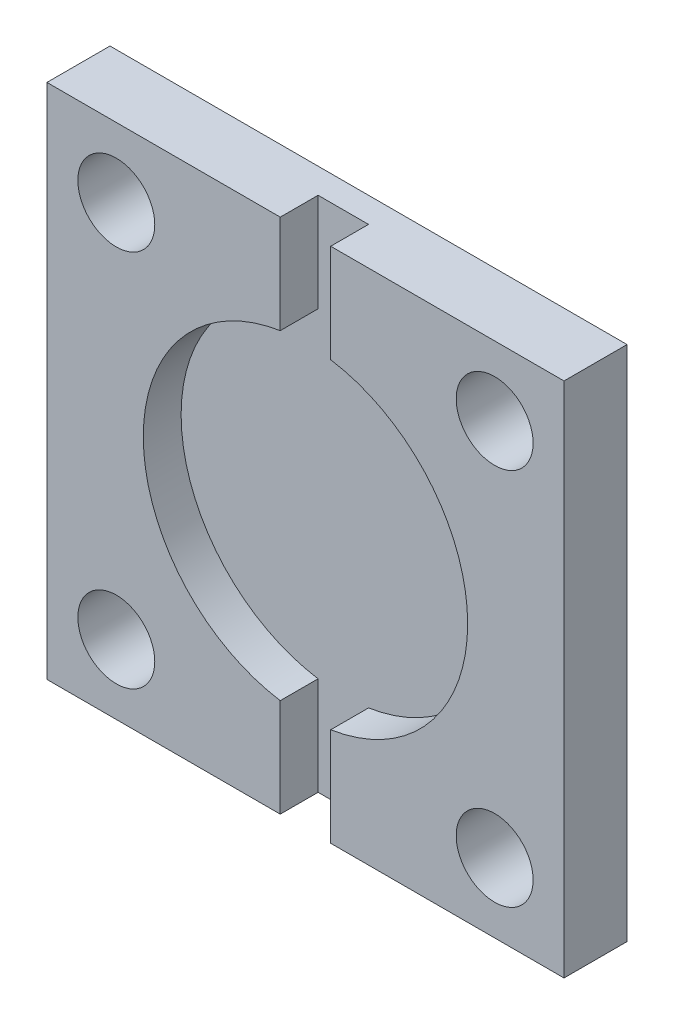
SolidWorks part; units mm, degrees
ref_plane "Alzado" through (0, 0, 0) normal (1, 0, 0) x (0, 1, 0)
ref_plane "Planta" through (0, 0, 0) normal (0, 0, 1) x (0, 1, 0)
ref_plane "Vista lateral" through (0, 0, 0) normal (0, 1, 0) x (-1, 0, 0)
sketch "Croquis1" plane through (0, 0, 0) normal (0, 0, 1) x (0, 1, 0)
  line L1 (0, 0) -> (41, 0)
  line L2 (0, 0) -> (0, 41)
  line L3 (0, 41) -> (41, 41)
  line L4 (41, 0) -> (41, 41)
extrude "PlaqueBase" add sketch "Croquis1" along normal blind 5 contours L2 L1 L4 L3
sketch "Croquis2" plane through (0, 0, 5) normal (0, 0, 1) x (1, 0, 0)
  line L0 (0, 41) -> (-41, 0) construction
  line L1 (0, 0) -> (-41, 0) construction
  line L2 (-41, 41) -> (0, 0) construction
  circle A0 centre (-20.5, 20.5) radius 12.86
extrude "CercleCentral" cut sketch "Croquis2" against normal blind 3
sketch "Croquis3" plane through (0, 0, 5) normal (0, 0, 1) x (1, 0, 0)
  circle A0 centre (-5.5, 35.5) radius 3.05
  circle A1 centre (-35.5, 35.5) radius 3.05
  circle A2 centre (-35.5, 5.5) radius 3.05
  circle A3 centre (-5.5, 5.5) radius 3.05
extrude "Support" cut sketch "Croquis3" against normal blind 5 contours A2 | A3 | A0 | A1
sketch "Croquis4" plane through (0, 0, 0) normal (0, -1, 0) x (-1, 0, 0)
  line L0 (41, -5) -> (0, 0)
  line L1 (20.5, -2.5) -> (20.5, -5) construction
  line L2 (0, -5) -> (41, -5) construction
  line L4 (22, -2.5) -> (19, -2.5)
  line L5 (22, -2.5) -> (22, -5)
  line L6 (22, -5) -> (19, -5)
  line L7 (19, -2.5) -> (19, -5)
  line L8 (22, -2.5) -> (19, -5) construction
  line L9 (22, -5) -> (19, -2.5) construction
  point P8 (20.5, -3.75)
extrude "TrousLat" cut sketch "Croquis4" against normal blind 41 contours L5 L4 L7 L6
sketch "Croquis6" plane through (0, 0, 2.5) normal (0, 0, 1) x (1, 0, 0)
  line L3 (-19, 33.2722) -> (-19, 41)
  line L4 (-19, 41) -> (-22, 41)
  line L5 (-22, 41) -> (-22, 33.2722)
  line L6 (-19, 33.2722) -> (-19, 41)
  line L7 (-19, 41) -> (-22, 41)
  line L8 (-22, 41) -> (-22, 33.2722)
  arc A1 (-19, 33.2722) -> (-22, 33.2722) centre (-20.5, 20.5) ccw
  arc A2 (-19, 33.2722) -> (-22, 33.2722) centre (-20.5, 20.5) ccw
  dimension "D1" = 0
extrude "Cortar-Extruir1" cut sketch "Croquis6" against normal blind 0.5
sketch "Croquis14" plane through (0, 0, 2.5) normal (0, 0, 1) x (1, 0, 0)
  line L3 (-22, 7.7278) -> (-22, 0)
  line L4 (-22, 0) -> (-19, 0)
  line L5 (-19, 0) -> (-19, 7.7278)
  line L6 (-22, 7.7278) -> (-22, 0)
  line L7 (-22, 0) -> (-19, 0)
  line L8 (-19, 0) -> (-19, 7.7278)
  arc A1 (-22, 7.7278) -> (-19, 7.7278) centre (-20.5, 20.5) ccw
  arc A2 (-22, 7.7278) -> (-19, 7.7278) centre (-20.5, 20.5) ccw
  dimension "D1" = 0
extrude "Cortar-Extruir2" cut sketch "Croquis14" against normal blind 0.5
sketch "Croquis15" plane through (-19, 0, 0) normal (-1, 0, 0) x (0, -1, 0)
  line L4 (-33.2722, 5) -> (-41, 5)
  line L5 (-41, 5) -> (-41, 2)
  line L6 (-41, 2) -> (-33.2722, 2)
  line L7 (-33.2722, 2) -> (-33.2722, 5)
  line L8 (-33.2722, 5) -> (-41, 5)
  line L9 (-41, 5) -> (-41, 2)
  line L10 (-41, 2) -> (-33.2722, 2)
  line L11 (-33.2722, 2) -> (-33.2722, 5)
  dimension "D1" = 0
extrude "Cortar-Extruir3" cut sketch "Croquis15" against normal blind 0.5
sketch "Croquis16" plane through (-19, 0, 0) normal (-1, 0, 0) x (0, -1, 0)
  line L4 (-7.7278, 5) -> (-7.7278, 2)
  line L5 (-7.7278, 2) -> (0, 2)
  line L6 (0, 2) -> (0, 5)
  line L7 (0, 5) -> (-7.7278, 5)
  line L8 (-7.7278, 5) -> (-7.7278, 2)
  line L9 (-7.7278, 2) -> (0, 2)
  line L10 (0, 2) -> (0, 5)
  line L11 (0, 5) -> (-7.7278, 5)
  dimension "D1" = 0
extrude "Cortar-Extruir4" cut sketch "Croquis16" against normal blind 0.5
sketch "Croquis17" plane through (-22, 0, 0) normal (1, 0, 0) x (0, 1, 0)
  line L4 (7.7278, 2) -> (7.7278, 5)
  line L5 (7.7278, 5) -> (0, 5)
  line L6 (0, 5) -> (0, 2)
  line L7 (0, 2) -> (7.7278, 2)
  line L8 (7.7278, 2) -> (7.7278, 5)
  line L9 (7.7278, 5) -> (0, 5)
  line L10 (0, 5) -> (0, 2)
  line L11 (0, 2) -> (7.7278, 2)
  dimension "D1" = 0
extrude "Cortar-Extruir5" cut sketch "Croquis17" against normal blind 0.5
sketch "Croquis18" plane through (-22, 0, 0) normal (1, 0, 0) x (0, 1, 0)
  line L4 (33.2722, 5) -> (33.2722, 2)
  line L5 (33.2722, 2) -> (41, 2)
  line L6 (41, 2) -> (41, 5)
  line L7 (41, 5) -> (33.2722, 5)
  line L8 (33.2722, 5) -> (33.2722, 2)
  line L9 (33.2722, 2) -> (41, 2)
  line L10 (41, 2) -> (41, 5)
  line L11 (41, 5) -> (33.2722, 5)
  dimension "D1" = 0
extrude "Cortar-Extruir6" cut sketch "Croquis18" against normal blind 0.5
sketch "Croquis19" plane through (0, 7.7278, 0) normal (0, -1, 0) x (1, 0, 0)
  line L4 (-22, 2) -> (-22, 5)
  line L5 (-22, 5) -> (-22.5, 5)
  line L6 (-22.5, 5) -> (-22.5, 2)
  line L7 (-22.5, 2) -> (-22, 2)
  line L8 (-22, 2) -> (-22, 5)
  line L9 (-22, 5) -> (-22.5, 5)
  line L10 (-22.5, 5) -> (-22.5, 2)
  line L11 (-22.5, 2) -> (-22, 2)
  dimension "D1" = 0
extrude "Cortar-Extruir7" cut sketch "Croquis19" against normal blind 0.5
sketch "Croquis20" plane through (0, 7.7278, 0) normal (0, -1, 0) x (1, 0, 0)
  line L4 (-19, 5) -> (-19, 2)
  line L5 (-19, 2) -> (-18.5, 2)
  line L6 (-18.5, 2) -> (-18.5, 5)
  line L7 (-18.5, 5) -> (-19, 5)
  line L8 (-19, 5) -> (-19, 2)
  line L9 (-19, 2) -> (-18.5, 2)
  line L10 (-18.5, 2) -> (-18.5, 5)
  line L11 (-18.5, 5) -> (-19, 5)
  dimension "D1" = 0
extrude "Cortar-Extruir8" cut sketch "Croquis20" against normal blind 0.5
sketch "Croquis21" plane through (0, 33.2722, 0) normal (0, 1, 0) x (-1, 0, 0)
  line L4 (19, 2) -> (19, 5)
  line L5 (19, 5) -> (18.5, 5)
  line L6 (18.5, 5) -> (18.5, 2)
  line L7 (18.5, 2) -> (19, 2)
  line L8 (19, 2) -> (19, 5)
  line L9 (19, 5) -> (18.5, 5)
  line L10 (18.5, 5) -> (18.5, 2)
  line L11 (18.5, 2) -> (19, 2)
  dimension "D1" = 0
extrude "Cortar-Extruir9" cut sketch "Croquis21" against normal blind 0.5
sketch "Croquis22" plane through (0, 33.2722, 0) normal (0, 1, 0) x (-1, 0, 0)
  line L4 (22, 5) -> (22, 2)
  line L5 (22, 2) -> (22.5, 2)
  line L6 (22.5, 2) -> (22.5, 5)
  line L7 (22.5, 5) -> (22, 5)
  line L8 (22, 5) -> (22, 2)
  line L9 (22, 2) -> (22.5, 2)
  line L10 (22.5, 2) -> (22.5, 5)
  line L11 (22.5, 5) -> (22, 5)
  dimension "D1" = 0
extrude "Cortar-Extruir10" cut sketch "Croquis22" against normal blind 0.5
